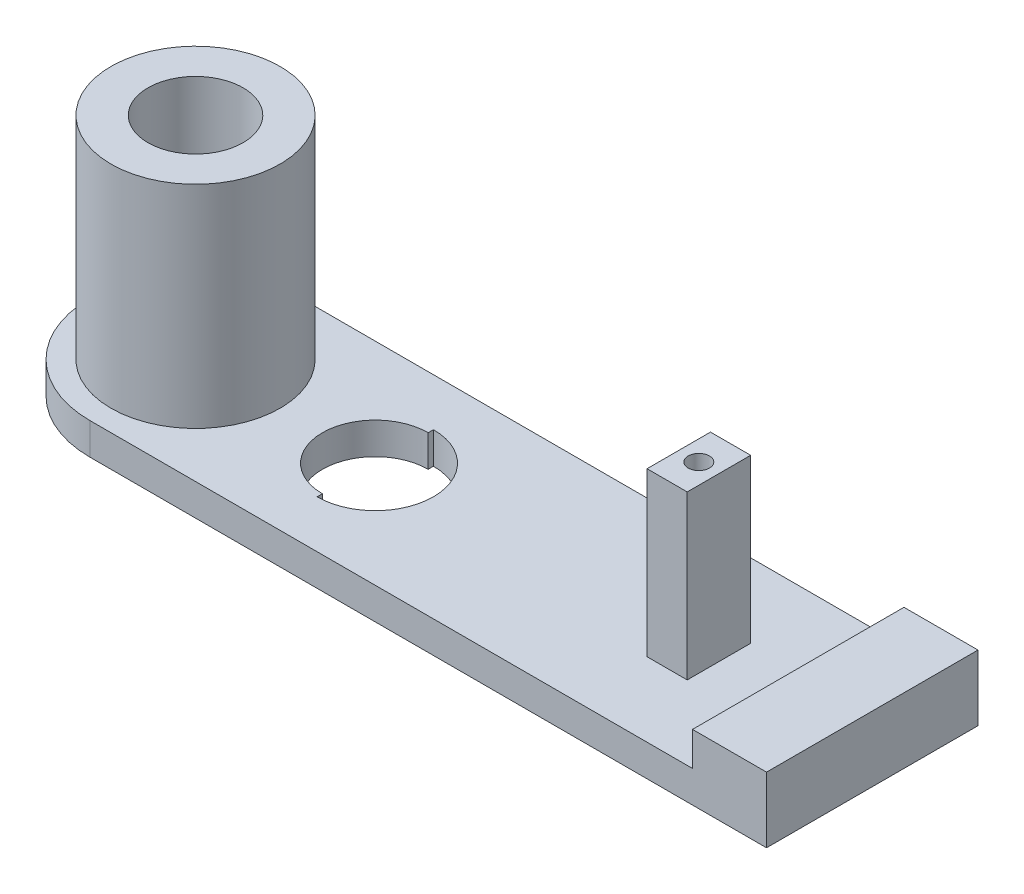
SolidWorks part; units mm, degrees
ref_plane "Front Plane" through (0, 0, 0) normal (0, 0, 1) x (1, 0, 0)
ref_plane "Top Plane" through (0, 0, 0) normal (0, 1, 0) x (1, 0, 0)
ref_plane "Right Plane" through (0, 0, 0) normal (1, 0, 0) x (0, 0, -1)
sketch "Sketch2" plane through (0, 0, 0) normal (0, 1, 0) x (1, 0, 0)
  line L1 (-160, 50) -> (160, 50)
  line L3 (-160, -50) -> (160, -50)
  line L4 (160, 50) -> (160, -50)
  line L5 (-160, 50) -> (160, -50) construction
  line L6 (-160, -50) -> (160, 50) construction
  arc A0 (-160, 50) -> (-160, -50) centre (-160, 0) ccw
  point P0 (0, 0)
  point P7 (-210, 0)
  dimension "D1" = 100
  dimension "D2" = 370
extrude "Boss-Extrude1" add sketch "Sketch2" along normal blind 15
sketch "Sketch3" plane through (0, 15, 0) normal (0, 1, 0) x (1, 0, 0)
  circle A0 centre (-160, 0) radius 40
  dimension "D1" = 80
extrude "Boss-Extrude2" add sketch "Sketch3" along normal blind 100
hole_wizard "Tap Drill for M30x2.0 Tap1" positions "3DSketch1" profile "Sketch4" hole size "M30x2.0" standard "ANSI Metric" end condition through all
sketch3d "3DSketch1"
  line L0 (-160, 115, 0) -> (-160, 15, 0) construction
  point P0 (-160, 115, 0)
sketch "Sketch4" plane through (-160, 115, 0) normal (1, 0, 0) x (0, 0, 1)
  line L0 (0, 0) -> (0, 115)
  line L1 (0, 115) -> (14, 115)
  line L2 (14, 115) -> (14, 0)
  line L5 (14, 0) -> (0, 0)
  line L11 (0, -6.35) -> (0, 107.95) construction
  dimension "Thru Hole Dia." = 28
  dimension "Thru Hole Depth" = 115
sketch "Sketch5" plane through (0, 115, 0) normal (0, 1, 0) x (1, 0, 0)
  circle A0 centre (-160, 0) radius 22.5
  dimension "D1" = 45
extrude "Cut-Extrude1" cut sketch "Sketch5" against normal blind 50
sketch "Sketch6" plane through (0, 15, 0) normal (0, 1, 0) x (1, 0, 0)
  line L0 (160, 50) -> (-160, 50) construction
  line L1 (160, -50) -> (125, -50)
  line L2 (160, -50) -> (160, 50)
  line L3 (160, 50) -> (125, 50)
  line L4 (125, -50) -> (125, 50)
  dimension "D1" = 35
extrude "Boss-Extrude3" add sketch "Sketch6" along normal blind 16
sketch "Sketch7" plane through (0, 15, 0) normal (0, 1, 0) x (1, 0, 0)
  circle A0 centre (-75, 0) radius 15
  circle A1 centre (-160, 0) radius 14 construction
  dimension "D1" = 30
  dimension "D2" = 85
extrude "Cut-Extrude2" cut sketch "Sketch7" against normal through all
sketch "Sketch8" plane through (0, 15, 0) normal (0, 1, 0) x (1, 0, 0)
  line L1 (68.5, 15) -> (87.5, 15)
  line L2 (68.5, 15) -> (68.5, -15)
  line L3 (68.5, -15) -> (87.5, -15)
  line L4 (87.5, 15) -> (87.5, -15)
  line L5 (68.5, 15) -> (87.5, -15) construction
  line L6 (68.5, -15) -> (87.5, 15) construction
  circle A0 centre (-75, 0) radius 15 construction
  circle A1 centre (78, 0) radius 5
  point P0 (78, 0)
  dimension "D3" = 153
  dimension "D4" = 10
  dimension "D1" = 19
  dimension "D2" = 30
extrude "Boss-Extrude4" add sketch "Sketch8" along normal blind 77
sketch "Sketch9" plane through (0, 15, 0) normal (0, 1, 0) x (1, 0, 0)
  line L0 (-75, -27.5) -> (-75, -25)
  line L1 (-75, 27.5) -> (-75, 25)
  arc A0 (-75, -27.5) -> (-75, 27.5) centre (-75, 0) ccw
  arc A1 (-75, 25) -> (-75, -25) centre (-75, 0) ccw
  dimension "D1" = 55
  dimension "D2" = 50
extrude "Cut-Extrude3" cut sketch "Sketch9" against normal through all
sketch "Sketch10" plane through (0, 15, 0) normal (0, 1, 0) x (1, 0, 0)
  circle A1 centre (78, 0) radius 5
  circle A2 centre (78, 0) radius 5
  dimension "D1" = 0
extrude "Cut-Extrude4" cut sketch "Sketch10" against normal through all
fillet "Fillet1" radius 1 1 edges at (-160, 65, 22.5)
